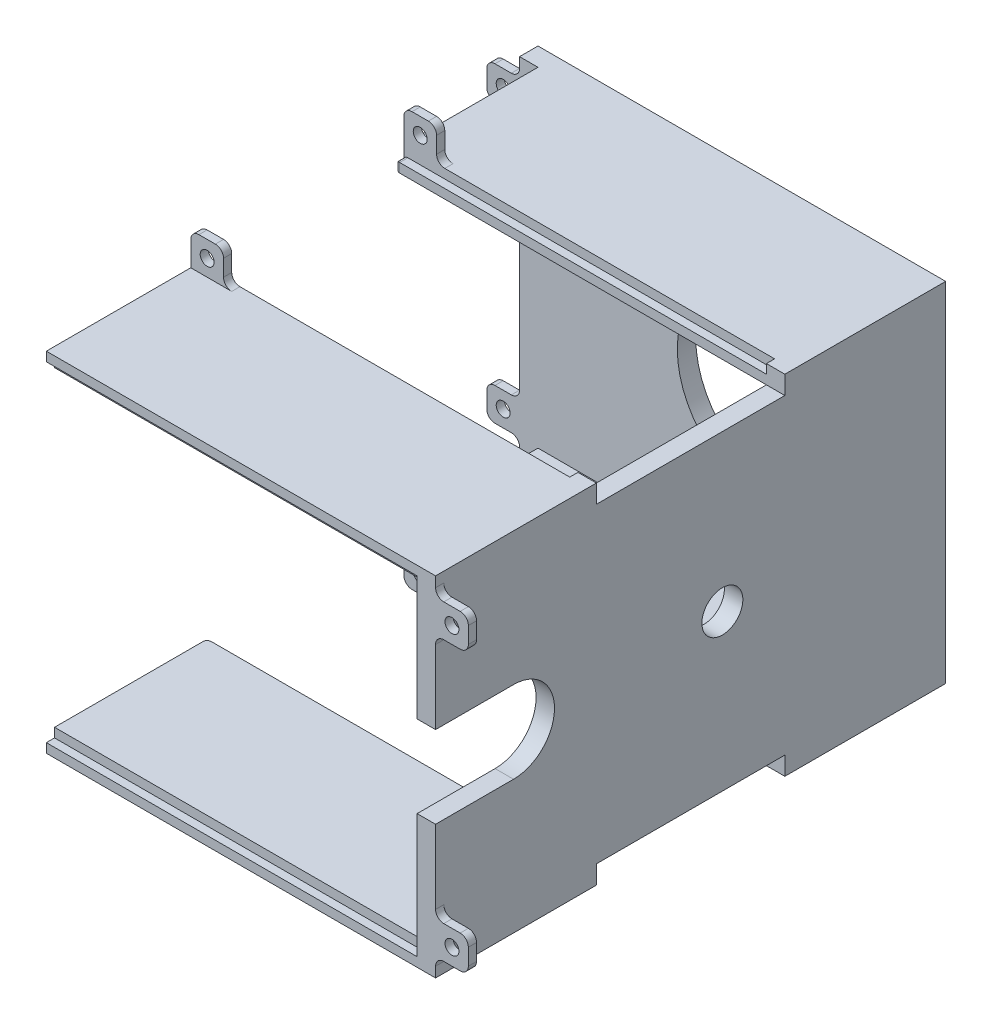
SolidWorks part; units mm, degrees
ref_plane "Front Plane" through (0, 0, 0) normal (1, 0, 0) x (0, 1, 0)
ref_plane "Top Plane" through (0, 0, 0) normal (0, 0, 1) x (0, 1, 0)
ref_plane "Right Plane" through (0, 0, 0) normal (0, 1, 0) x (-1, 0, 0)
sketch "Sketch1" plane through (0, 0, 0) normal (0, 0, 1) x (0, 1, 0)
  line L1 (-42.5, -47.5) -> (42.5, -47.5)
  line L2 (-42.5, -47.5) -> (-42.5, 47.5)
  line L3 (-42.5, 47.5) -> (42.5, 47.5)
  line L4 (42.5, -47.5) -> (42.5, 47.5)
  line L5 (-42.5, -47.5) -> (42.5, 47.5) construction
  line L6 (-42.5, 47.5) -> (42.5, -47.5) construction
  point P0 (0, 0)
  dimension "D1" = 85
  dimension "D2" = 95
extrude "Boss-Extrude1" add sketch "Sketch1" along normal blind 4.5
sketch "Sketch2" plane through (0, 0, 4.5) normal (0, 0, 1) x (1, 0, 0)
  line L0 (47.5, 42.5) -> (-47.5, 42.5) construction
  line L1 (47.5, -42.5) -> (43, -42.5)
  line L2 (47.5, -42.5) -> (47.5, 42.5)
  line L3 (47.5, 42.5) -> (43, 42.5)
  line L4 (43, -42.5) -> (43, 42.5)
  dimension "D1" = 4.5
extrude "Boss-Extrude2" add sketch "Sketch2" along normal blind 120
sketch "Sketch3" plane through (0, 0, 4.5) normal (0, 0, 1) x (1, 0, 0)
  line L0 (43, 42.5) -> (-47.5, 42.5)
  line L2 (-47.5, -42.5) -> (43, -42.5)
  line L3 (43, -42.5) -> (43, -38)
  line L4 (43, 42.5) -> (43, -42.5) construction
  line L5 (43, -38) -> (-47.5, -38)
  line L7 (-47.5, 38) -> (43, 38)
  line L8 (43, 38) -> (43, 42.5)
  line L9 (-47.5, 42.5) -> (-47.5, -42.5) construction
  line L10 (-47.5, 42.5) -> (-47.5, 38)
  line L11 (-47.5, -38) -> (-47.5, -42.5)
  dimension "D1" = 4.5
extrude "Boss-Extrude3" add sketch "Sketch3" along normal blind 120
sketch "Sketch4" plane through (0, 0, 0) normal (0, 0, -1) x (1, 0, 0)
  line L0 (-47.5, 0) -> (9, 0) construction
  line L1 (-47.5, -42.5) -> (-47.5, 42.5) construction
  line L2 (47.5, 42.5) -> (47.5, -42.5) construction
  circle A0 centre (9, 0) radius 22.5
  dimension "D1" = 45
  dimension "D2" = 38.5
extrude "Cut-Extrude1" cut sketch "Sketch4" against normal up to next
sketch "Sketch7" plane through (-47.5, 0, 0) normal (-1, 0, 0) x (0, -1, 0)
  line L0 (-38, 85.25) -> (-40.25, 85.25)
  line L1 (-38, 124.5) -> (-38, 4.5) construction
  line L2 (-40.25, 85.25) -> (-40.25, 87.25)
  line L3 (-40.25, 87.25) -> (-42.5, 87.25)
  line L4 (-42.5, 124.5) -> (-42.5, 0) construction
  line L5 (-42.5, 87.25) -> (-42.5, 37.25)
  line L6 (-42.5, 37.25) -> (-40.25, 37.25)
  line L7 (-40.25, 37.25) -> (-40.25, 39.25)
  line L8 (-40.25, 39.25) -> (-38, 39.25)
  line L9 (-38, 124.5) -> (-38, 4.5) construction
  line L10 (-38, 39.25) -> (-38, 85.25)
  line L11 (-42.5, 62.25) -> (-38, 62.25) construction
  line L12 (0, 0) -> (0, 4.5) construction
  line L13 (-38, 4.5) -> (38, 4.5) construction
  line L14 (40.25, 39.25) -> (38, 39.25)
  line L15 (40.25, 37.25) -> (40.25, 39.25)
  line L16 (42.5, 37.25) -> (40.25, 37.25)
  line L17 (42.5, 87.25) -> (42.5, 37.25)
  line L18 (40.25, 87.25) -> (42.5, 87.25)
  line L19 (40.25, 85.25) -> (40.25, 87.25)
  line L20 (38, 85.25) -> (40.25, 85.25)
  line L21 (38, 39.25) -> (38, 85.25)
  dimension "D1" = 2.25
  dimension "D2" = 2
  dimension "D3" = 50
extrude "Cut-Extrude3" cut sketch "Sketch7" against normal through all
sketch "Sketch8" plane through (-47.5, 0, 0) normal (-1, 0, 0) x (0, -1, 0)
  line L1 (-38, 124.5) -> (-40.25, 124.5)
  line L2 (-38, 124.5) -> (-38, 122.5)
  line L3 (-38, 122.5) -> (-40.25, 122.5)
  line L4 (-40.25, 124.5) -> (-40.25, 122.5)
  line L5 (38, 124.5) -> (40.25, 124.5)
  line L6 (38, 124.5) -> (38, 122.5)
  line L7 (38, 122.5) -> (40.25, 122.5)
  line L8 (40.25, 124.5) -> (40.25, 122.5)
  dimension "D1" = 2.25
  dimension "D2" = 2
  dimension "D3" = 2
  dimension "D4" = 2.25
extrude "Cut-Extrude4" cut sketch "Sketch8" against normal up to surface (90.5 mm away) up to face at (43, 0, 63.375)
sketch "Sketch9" plane through (-47.5, 0, 0) normal (-1, 0, 0) x (0, -1, 0)
  line L0 (42.5, 37.25) -> (42.5, 0) construction
  line L1 (-42.5, 0) -> (42.5, 0)
  line L2 (-42.5, 0) -> (-42.5, 4.5)
  line L3 (-42.5, 4.5) -> (42.5, 4.5)
  line L4 (42.5, 0) -> (42.5, 4.5)
  line L5 (-38, 4.5) -> (38, 4.5) construction
extrude "Boss-Extrude5" add sketch "Sketch9" along normal blind 4.5
sketch "Sketch11" plane through (43, 0, 0) normal (-1, 0, 0) x (0, -1, 0)
  line L0 (0, 4.5) -> (0, 54.5) construction
  line L1 (-20, 29.5) -> (20, 29.5)
  line L2 (-20, 29.5) -> (-20, 79.5)
  line L3 (-20, 79.5) -> (20, 79.5)
  line L4 (20, 29.5) -> (20, 79.5)
  line L5 (-20, 29.5) -> (20, 79.5) construction
  line L6 (-20, 79.5) -> (20, 29.5) construction
  line L7 (-38, 4.5) -> (38, 4.5) construction
  point P0 (0, 54.5)
  dimension "D1" = 40
  dimension "D2" = 50
  dimension "D3" = 50
extrude "Boss-Extrude7" add sketch "Sketch11" along normal blind 10
sketch "Sketch12" plane through (33, 0, 0) normal (-1, 0, 0) x (0, -1, 0)
  line L0 (0, 54.5) -> (0, 29.5) construction
  line L1 (-15.25, 34.25) -> (15.25, 34.25)
  line L2 (-15.25, 34.25) -> (-15.25, 74.75)
  line L3 (-15.25, 74.75) -> (15.25, 74.75)
  line L4 (15.25, 34.25) -> (15.25, 74.75)
  line L5 (-15.25, 34.25) -> (15.25, 74.75) construction
  line L6 (-15.25, 74.75) -> (15.25, 34.25) construction
  line L7 (-20, 29.5) -> (20, 29.5) construction
  line L8 (-20, 54.5) -> (0, 54.5) construction
  line L9 (-20, 79.5) -> (-20, 29.5) construction
  point P0 (0, 54.5)
  dimension "D1" = 40.5
  dimension "D2" = 30.5
extrude "Cut-Extrude5" cut sketch "Sketch12" against normal blind 10
sketch "Sketch13" plane through (43, 0, 0) normal (-1, 0, 0) x (0, -1, 0)
  line L0 (0, 54.5) -> (0, 34.25) construction
  line L1 (-15.25, 34.25) -> (15.25, 34.25) construction
  line L2 (0, 54.5) -> (15.25, 54.5) construction
  line L3 (15.25, 34.25) -> (15.25, 74.75) construction
  circle A0 centre (0, 54.5) radius 5
  dimension "D1" = 10
extrude "Cut-Extrude6" cut sketch "Sketch13" against normal through all
fillet "Fillet1" [suppressed] radius 1
sketch "Sketch14" plane through (47.5, 0, 0) normal (1, 0, 0) x (0, 1, 0)
  line L0 (-38, 62.25) -> (38, 62.25) construction
  line L5 (-38, 85.25) -> (-38, 39.25) construction
  line L6 (38, 39.25) -> (38, 85.25) construction
  line L7 (0, 124.5) -> (0, 0) construction
  line L8 (-42.5, 124.5) -> (42.5, 124.5) construction
  line L21 (-42.5, 124.5) -> (-42.5, 87.25) construction
  line L22 (-38, 124.5) -> (-30, 124.5)
  line L23 (-38, 124.5) -> (-38, 122.5)
  line L24 (-38, 122.5) -> (-30, 122.5)
  line L25 (-30, 124.5) -> (-30, 122.5)
  line L26 (38, 122.5) -> (30, 122.5)
  line L27 (30, 124.5) -> (30, 122.5)
  line L28 (38, 124.5) -> (30, 124.5)
  line L29 (38, 124.5) -> (38, 122.5)
  dimension "D3" = 4.5
  dimension "D4" = 2
  dimension "D5" = 8
extrude "Boss-Extrude8" add sketch "Sketch14" along normal blind 8
sketch "Sketch16" plane through (0, 0, 124.5) normal (0, 0, 1) x (1, 0, 0)
  line L0 (47.5, 0) -> (43, 0) construction
  line L1 (47.5, -30) -> (47.5, 30) construction
  line L2 (43, 40.25) -> (43, -40.25) construction
  line L3 (51.5, 38) -> (51.5, 30) construction
  line L4 (55.5, 38) -> (47.5, 38) construction
  line L5 (55.5, 30) -> (47.5, 30) construction
  line L6 (55.5, 34) -> (43, 34) construction
  line L7 (55.5, 38) -> (55.5, 30) construction
  circle A0 centre (51.5, 34) radius 1.7
  circle A1 centre (51.5, -34) radius 1.7
  dimension "D1" = 3.4
extrude "Cut-Extrude8" cut sketch "Sketch16" against normal through all both and the other way through all
sketch "Sketch17" plane through (-52, 0, 0) normal (-1, 0, 0) x (0, -1, 0)
  line L0 (0, 0) -> (0, 4.5) construction
  line L1 (-38, 4.5) -> (-30, 4.5)
  line L2 (-38, 4.5) -> (-38, 2.5)
  line L3 (-38, 2.5) -> (-30, 2.5)
  line L4 (-30, 4.5) -> (-30, 2.5)
  line L5 (42.5, 4.5) -> (-42.5, 4.5) construction
  line L6 (38, 2.5) -> (30, 2.5)
  line L7 (30, 4.5) -> (30, 2.5)
  line L8 (38, 4.5) -> (30, 4.5)
  line L9 (38, 4.5) -> (38, 2.5)
  dimension "D1" = 2
  dimension "D2" = 8
extrude "Boss-Extrude9" add sketch "Sketch17" along normal blind 8
sketch "Sketch18" plane through (0, 0, 2.5) normal (0, 0, -1) x (1, 0, 0)
  line L0 (-60, -34) -> (-52, -34) construction
  line L1 (-60, -38) -> (-60, -30) construction
  line L2 (-52, -38) -> (-52, -30) construction
  line L3 (-56, -30) -> (-56, -38) construction
  line L4 (-60, -30) -> (-52, -30) construction
  line L5 (-60, -38) -> (-52, -38) construction
  line L6 (-52, 0) -> (-13.5, 0) construction
  line L7 (-52, -42.5) -> (-52, 42.5) construction
  circle A0 centre (9, 0) radius 22.5 construction
  circle A1 centre (-56, -34) radius 1.7
  circle A2 centre (-56, 34) radius 1.7
  dimension "D1" = 3.4
extrude "Cut-Extrude9" cut sketch "Sketch18" against normal through all both and the other way through all
sketch "Sketch19" plane through (47.5, 0, 0) normal (1, 0, 0) x (0, 1, 0)
  line L1 (-40.25, 85.25) -> (-42.5, 85.25)
  line L2 (-40.25, 85.25) -> (-40.25, 87.25)
  line L3 (-40.25, 87.25) -> (-42.5, 87.25)
  line L4 (-42.5, 85.25) -> (-42.5, 87.25)
  line L5 (-42.5, 37.25) -> (-40.25, 37.25)
  line L6 (-42.5, 37.25) -> (-42.5, 39.25)
  line L7 (-42.5, 39.25) -> (-40.25, 39.25)
  line L8 (-40.25, 37.25) -> (-40.25, 39.25)
  line L9 (40.25, 39.25) -> (42.5, 39.25)
  line L10 (40.25, 39.25) -> (40.25, 37.25)
  line L11 (40.25, 37.25) -> (42.5, 37.25)
  line L12 (42.5, 39.25) -> (42.5, 37.25)
  line L13 (40.25, 85.25) -> (42.5, 85.25)
  line L14 (40.25, 85.25) -> (40.25, 87.25)
  line L15 (40.25, 87.25) -> (42.5, 87.25)
  line L16 (42.5, 85.25) -> (42.5, 87.25)
extrude "Boss-Extrude10" add sketch "Sketch19" against normal blind 4.5
sketch "Sketch20" plane through (0, 42.5, 0) normal (0, 1, 0) x (-1, 0, 0)
  line L0 (-47.5, 62.25) -> (-43, 62.25) construction
  line L1 (47.5, 37.25) -> (39.5, 37.25)
  line L2 (47.5, 37.25) -> (47.5, 35.25)
  line L3 (47.5, 35.25) -> (39.5, 35.25)
  line L4 (39.5, 37.25) -> (39.5, 35.25)
  line L5 (-47.5, 39.25) -> (-47.5, 85.25) construction
  line L6 (-43, 85.25) -> (-43, 39.25) construction
  line L7 (47.5, 89.25) -> (39.5, 89.25)
  line L8 (39.5, 87.25) -> (39.5, 89.25)
  line L9 (47.5, 87.25) -> (39.5, 87.25)
  line L10 (47.5, 87.25) -> (47.5, 89.25)
  dimension "D1" = 2
  dimension "D2" = 8
extrude "Boss-Extrude11" add sketch "Sketch20" along normal blind 8
sketch "Sketch22" plane through (0, -42.5, 0) normal (0, -1, 0) x (1, 0, 0)
  line L1 (-47.5, 37.25) -> (-39.5, 37.25)
  line L2 (-47.5, 37.25) -> (-47.5, 35.25)
  line L3 (-47.5, 35.25) -> (-39.5, 35.25)
  line L4 (-39.5, 37.25) -> (-39.5, 35.25)
  line L5 (-47.5, 87.25) -> (-39.5, 87.25)
  line L6 (-47.5, 87.25) -> (-47.5, 89.25)
  line L7 (-47.5, 89.25) -> (-39.5, 89.25)
  line L8 (-39.5, 87.25) -> (-39.5, 89.25)
  dimension "D1" = 2
  dimension "D2" = 8
  dimension "D3" = 8
  dimension "D4" = 2
extrude "Boss-Extrude12" add sketch "Sketch22" along normal blind 8
sketch "Sketch21" plane through (0, 0, 35.25) normal (0, 0, -1) x (1, 0, 0)
  line L0 (-43.5, -42.5) -> (-43.5, -50.5) construction
  line L1 (-39.5, -42.5) -> (-47.5, -42.5) construction
  line L2 (-39.5, -50.5) -> (-47.5, -50.5) construction
  line L3 (-47.5, -46.5) -> (-39.5, -46.5) construction
  line L4 (-47.5, -50.5) -> (-47.5, -42.5) construction
  line L5 (-39.5, -50.5) -> (-39.5, -42.5) construction
  line L6 (-52, 0) -> (-13.5, 0) construction
  line L7 (-52, -42.5) -> (-52, 42.5) construction
  circle A0 centre (-43.5, -46.5) radius 1.7
  circle A1 centre (9, 0) radius 22.5 construction
  circle A2 centre (-43.5, 46.5) radius 1.7
  dimension "D1" = 3.4
extrude "Cut-Extrude10" cut sketch "Sketch21" against normal through all both and the other way through all
fillet "Fillet2" radius 2 28 edges at (47.5, -30, 123.5) (55.5, -30, 123.5) (55.5, -38, 123.5) (47.5, -38, 123.5) (55.5, 30, 123.5) (47.5, 30, 123.5) (55.5, 38, 123.5) (47.5, 38, 123.5) (-52, -38, 3.5) (-60, -38, 3.5) (-60, -30, 3.5) (-52, -30, 3.5) (-60, 38, 3.5) (-52, 38, 3.5) (-52, 30, 3.5) (-60, 30, 3.5) (-47.5, -50.5, 88.25) (-39.5, -50.5, 88.25) (-39.5, -42.5, 88.25) (-47.5, -50.5, 36.25) (-39.5, -50.5, 36.25) (-39.5, -42.5, 36.25) (-47.5, 50.5, 88.25) (-39.5, 50.5, 88.25) (-39.5, 42.5, 88.25) (-39.5, 42.5, 36.25) (-39.5, 50.5, 36.25) (-47.5, 50.5, 36.25)
fillet "Fillet3" radius 1 8 edges at (-47.5, -39.125, 39.25) (-47.5, 39.125, 85.25) (-47.5, 40.25, 86.25) (-47.5, 40.25, 38.25) (-47.5, 39.125, 39.25) (-47.5, -40.25, 38.25) (-47.5, -40.25, 86.25) (-47.5, -39.125, 85.25)
sketch "Sketch23" plane through (43, 0, 0) normal (-1, 0, 0) x (0, -1, 0)
  line L0 (0, 124.5) -> (0, 105.4727) construction
  line L1 (-40.25, 124.5) -> (40.25, 124.5) construction
  line L2 (-10, 124.5) -> (-10, 105.4727)
  line L3 (10, 105.4727) -> (10, 124.5)
  line L4 (10, 124.5) -> (-10, 124.5)
  arc A0 (-10, 105.4727) -> (10, 105.4727) centre (0, 105.4727) ccw
  point P9 (0, 0)
  dimension "D1" = 10
extrude "Cut-Extrude11" cut sketch "Sketch23" against normal through all both and the other way through all
